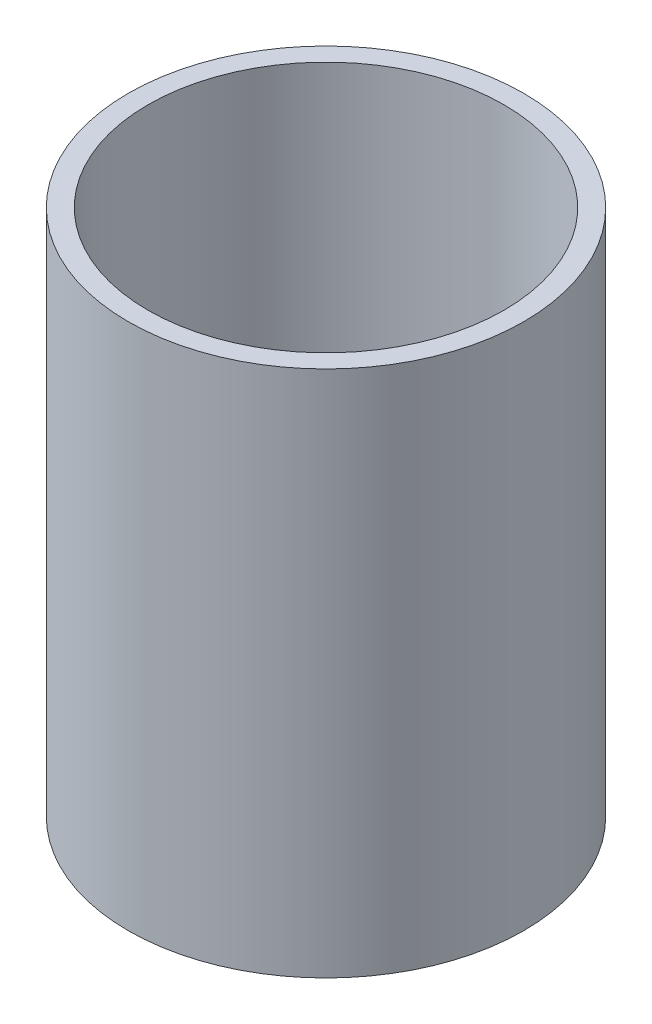
SolidWorks part; units mm, degrees
ref_plane "정면" through (0, 0, 0) normal (0, 0, 1) x (1, 0, 0)
ref_plane "윗면" through (0, 0, 0) normal (0, 1, 0) x (1, 0, 0)
ref_plane "우측면" through (0, 0, 0) normal (1, 0, 0) x (0, 0, -1)
sketch "스케치1" plane through (0, 0, 0) normal (0, 1, 0) x (1, 0, 0)
  circle A0 centre (0, 0) radius 30
  circle A1 centre (0, 0) radius 27
  dimension "D1" = 60
  dimension "D2" = 3
extrude "보스-돌출1" add sketch "스케치1" along normal blind 80
